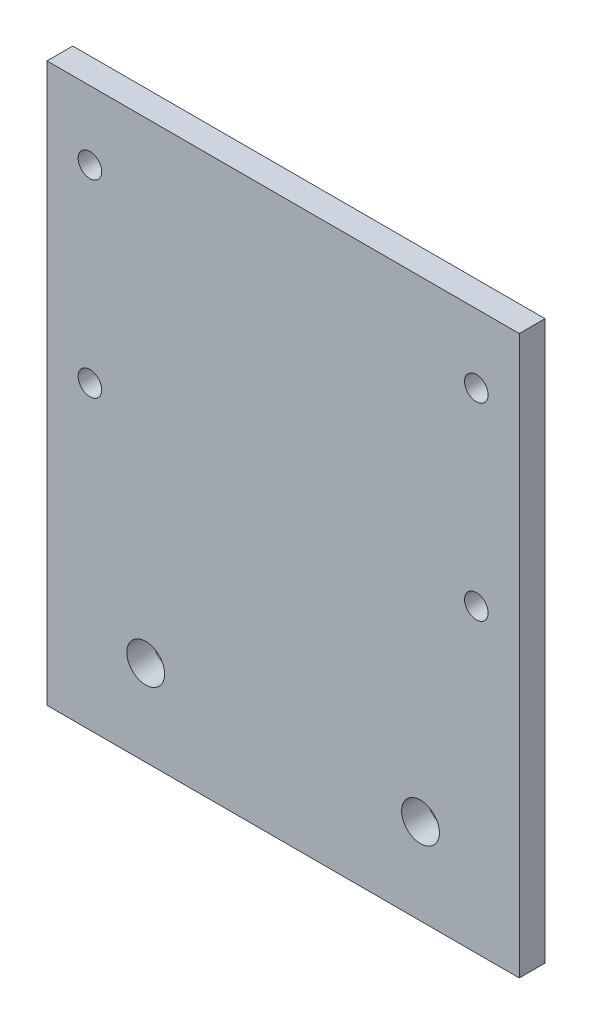
SolidWorks part; units mm, degrees
ref_plane "Front Plane" through (0, 0, 0) normal (0, 0, 1) x (1, 0, 0)
ref_plane "Top Plane" through (0, 0, 0) normal (0, 1, 0) x (1, 0, 0)
ref_plane "Right Plane" through (0, 0, 0) normal (1, 0, 0) x (0, 0, -1)
sketch "Sketch1" plane through (0, 0, 0) normal (0, 0, 1) x (1, 0, 0)
  line L0 (27.5, 65) -> (27.5, 0) construction
  line L1 (0, 0) -> (55, 0)
  line L2 (0, 0) -> (0, 65)
  line L3 (0, 65) -> (55, 65)
  line L4 (55, 0) -> (55, 65)
  line L5 (5, 57) -> (50, 57) construction
  line L6 (5, 57) -> (5, 35) construction
  line L7 (5, 35) -> (50, 35) construction
  line L8 (50, 57) -> (50, 35) construction
  line L9 (11.5, 10) -> (43.5, 10) construction
  circle A0 centre (5, 57) radius 1.375
  circle A1 centre (50, 57) radius 1.375
  circle A2 centre (50, 35) radius 1.375
  circle A3 centre (5, 35) radius 1.375
  circle A4 centre (11.5, 10) radius 2.2
  circle A5 centre (43.5, 10) radius 2.2
  point P11 (27.5, 57)
  point P23 (27.5, 10)
  point P24 (0, 0)
  dimension "D6" = 2.75
  dimension "D9" = 4.4
  dimension "D10" = 4.4
  dimension "D1" = 55
  dimension "D2" = 65
  dimension "D3" = 45
  dimension "D4" = 22
  dimension "D5" = 35
  dimension "D11" = 32
  dimension "D12" = 20
  dimension "D7" = 2
  dimension "D8" = 2
extrude "Boss-Extrude1" add sketch "Sketch1" along normal blind 3
